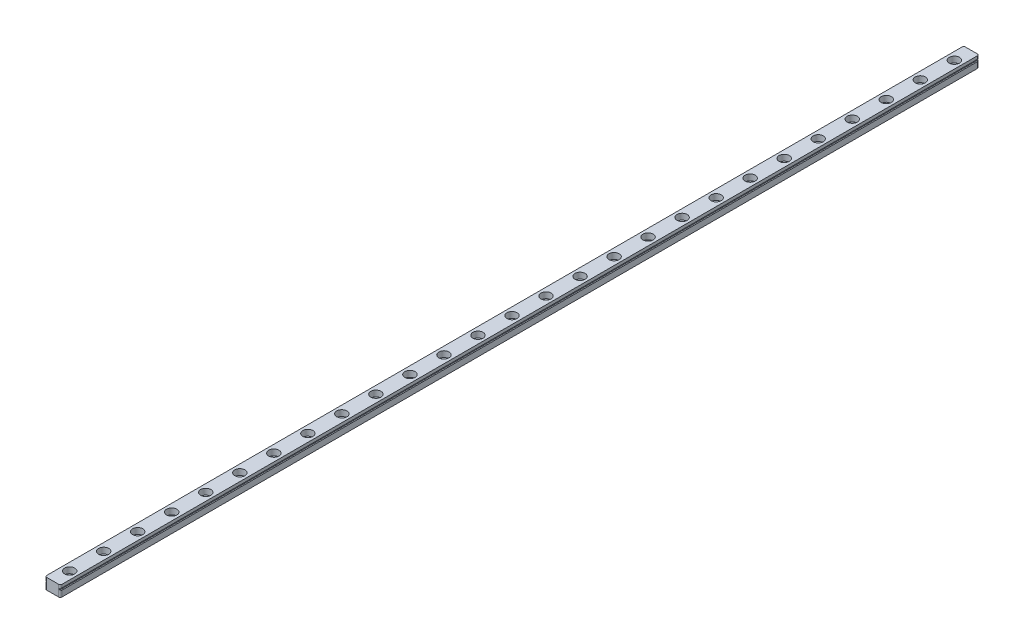
SolidWorks part; units mm, degrees
material "镀铬不锈钢"
ref_plane "前视基准面" through (0, 0, 0) normal (0, 0, 1) x (1, 0, 0)
ref_plane "上视基准面" through (0, 0, 0) normal (0, 1, 0) x (1, 0, 0)
ref_plane "右视基准面" through (0, 0, 0) normal (1, 0, 0) x (0, 0, -1)
sketch "草图1" plane through (0, 0, 0) normal (0, 0, 1) x (1, 0, 0)
  line L0 (-4.5, -3.6634) -> (4.5, -3.6634)
  line L1 (0, -3.6634) -> (0, 3.6634) construction
  line L2 (4.5, -3.6634) -> (4.5, -0.1634)
  line L3 (4.5, -0.1634) -> (4.1464, 0.1901)
  line L4 (4.1464, 0.1901) -> (3.6464, 0.1901)
  line L5 (3.6464, 0.1901) -> (3.6464, 0.6901)
  line L6 (3.6464, 0.6901) -> (4.1464, 0.6901)
  line L7 (4.1464, 0.6901) -> (4.5, 1.0437)
  line L8 (4.5, 1.0437) -> (4.5, 2.8366)
  line L9 (4.5, 2.8366) -> (-4.5, 2.8366)
  line L10 (-4.5, 1.0437) -> (-4.5, 2.8366)
  line L11 (-4.1464, 0.6901) -> (-4.5, 1.0437)
  line L12 (-3.6464, 0.6901) -> (-4.1464, 0.6901)
  line L13 (-3.6464, 0.1901) -> (-3.6464, 0.6901)
  line L14 (-4.1464, 0.1901) -> (-3.6464, 0.1901)
  line L15 (-4.5, -0.1634) -> (-4.1464, 0.1901)
  line L16 (-4.5, -3.6634) -> (-4.5, -0.1634)
  point P13 (0, 2.8366)
extrude "凸台-拉伸1" add sketch "草图1" along normal blind 540
sketch "草图2" plane through (0, 2.8366, 0) normal (0, 1, 0) x (1, 0, 0)
  line L0 (-4.5, -540) -> (-4.5, 0) construction
  line L1 (4.5, -540) -> (-4.5, -540) construction
  circle A0 centre (0, -530) radius 3
  dimension "D1" = 6
  dimension "D2" = 4.5
  dimension "D3" = 10
extrude "切除-拉伸1" cut sketch "草图2" against normal blind 3.5
sketch "草图3" plane through (0, -0.6634, 0) normal (0, 1, 0) x (1, 0, 0)
  circle A0 centre (0, -530) radius 1.75
  dimension "D1" = 3.5
extrude "切除-拉伸2" cut sketch "草图3" against normal through all
pattern_linear "阵列(线性)1" count 30 spacing 20 along (0, 0, -1) of "切除-拉伸1", "切除-拉伸2"
fillet "圆角1" radius 1 4 edges at (4.5, -1.9134, 0) (-4.5, -1.9134, 0) (4.5, -1.9134, 540) (-4.5, -1.9134, 540)
